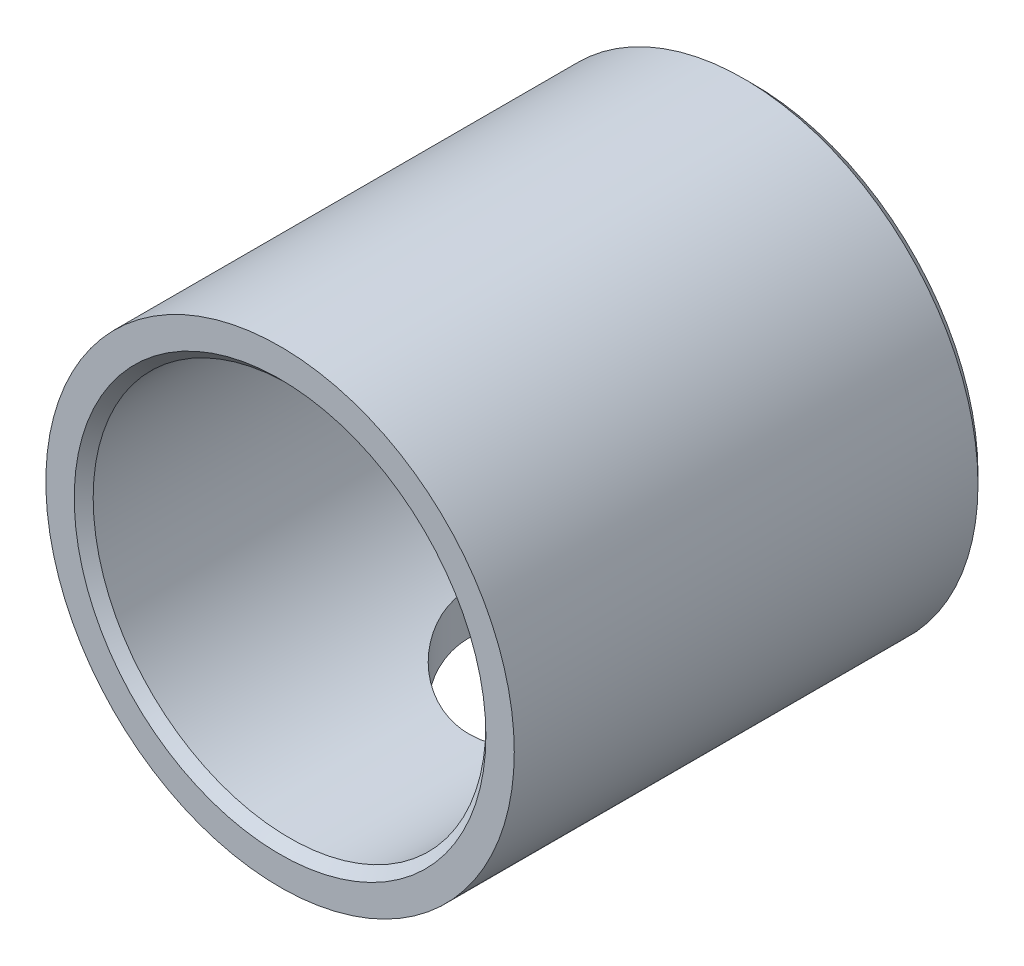
SolidWorks part; units mm, degrees
ref_plane "Front Plane" through (0, 0, 0) normal (0, 0, 1) x (1, 0, 0)
ref_plane "Top Plane" through (0, 0, 0) normal (0, 1, 0) x (1, 0, 0)
ref_plane "Right Plane" through (0, 0, 0) normal (1, 0, 0) x (0, 0, -1)
sketch "Sketch1" plane through (0, 0, 0) normal (0, 0, 1) x (1, 0, 0)
  circle A0 centre (0, 0) radius 4.95
  circle A1 centre (0, 0) radius 4.15
  dimension "D1" = 9.9
  dimension "D2" = 8.3
extrude "Boss-Extrude1" add sketch "Sketch1" along normal blind 10
chamfer "Chamfer1" distance 0.2 angle 45 3 edges at (4.15, 0, 0) (4.95, 0, 0) (4.15, 0, 10)
sketch "Sketch2" plane through (0, 0, 0) normal (0, 1, 0) x (1, 0, 0)
  line L0 (0, 2.4955) -> (0, -12.1746) construction
  line L1 (-10.3608, 0) -> (7.4726, 0) construction
  circle A0 centre (0, -3.9) radius 2.1
  dimension "D1" = 3.9
  dimension "D2" = 4.2
extrude "Cut-Extrude1" cut sketch "Sketch2" against normal through all
